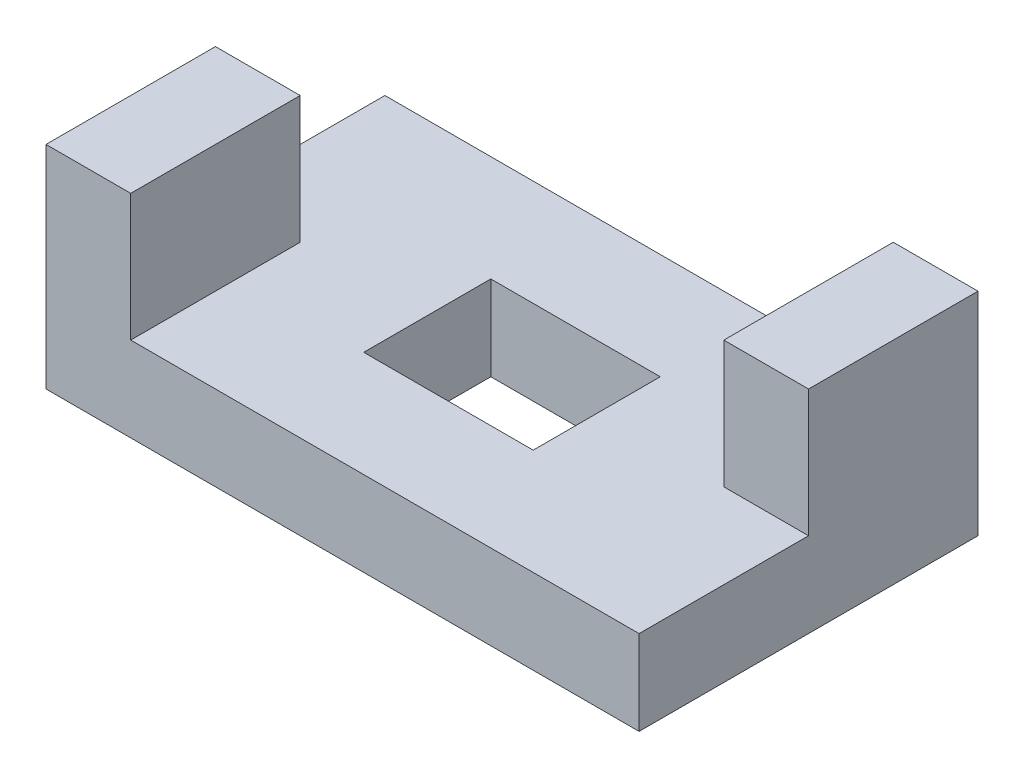
SolidWorks part; units mm, degrees
ref_plane "Front Plane" through (0, 0, 0) normal (0, 0, 1) x (1, 0, 0)
ref_plane "Top Plane" through (0, 0, 0) normal (0, 1, 0) x (1, 0, 0)
ref_plane "Right Plane" through (0, 0, 0) normal (1, 0, 0) x (0, 0, -1)
sketch "Sketch1" plane through (0, 0, 0) normal (0, 1, 0) x (1, 0, 0)
  line L1 (0, 0) -> (112, 0)
  line L2 (0, 0) -> (0, 64)
  line L3 (0, 64) -> (112, 64)
  line L4 (112, 0) -> (112, 64)
  dimension "D1" = 112
  dimension "D2" = 64
extrude "Boss-Extrude1" add sketch "Sketch1" along normal blind 16
sketch "Sketch3" plane through (0, 0, 0) normal (0, 0, 1) x (1, 0, 0)
  line L1 (0, 0) -> (16, 0)
  line L2 (0, 0) -> (0, 40)
  line L3 (0, 40) -> (16, 40)
  line L4 (16, 0) -> (16, 40)
  dimension "D1" = 40
  dimension "D2" = 16
extrude "Boss-Extrude2" add sketch "Sketch3" against normal blind 32
sketch "Sketch6" plane through (0, 0, -64) normal (0, 0, -1) x (-1, 0, 0)
  line L1 (-112, 0) -> (-96, 0)
  line L2 (-112, 0) -> (-112, 40)
  line L3 (-112, 40) -> (-96, 40)
  line L4 (-96, 0) -> (-96, 40)
  dimension "D1" = 40
  dimension "D2" = 16
extrude "Boss-Extrude3" add sketch "Sketch6" against normal blind 32
sketch "Sketch7" plane through (0, 16, 0) normal (0, 1, 0) x (1, 0, 0)
  line L0 (96, 64) -> (0, 64) construction
  line L1 (40, 44) -> (72, 44)
  line L2 (40, 44) -> (40, 20)
  line L3 (40, 20) -> (72, 20)
  line L4 (72, 44) -> (72, 20)
  line L5 (40, 44) -> (72, 20) construction
  line L6 (40, 20) -> (72, 44) construction
  line L7 (0, 32) -> (0, 0) construction
  point P0 (56, 32)
  dimension "D1" = 32
  dimension "D2" = 24
  dimension "D3" = 20
  dimension "D4" = 40
extrude "Cut-Extrude1" cut sketch "Sketch7" against normal up to next
